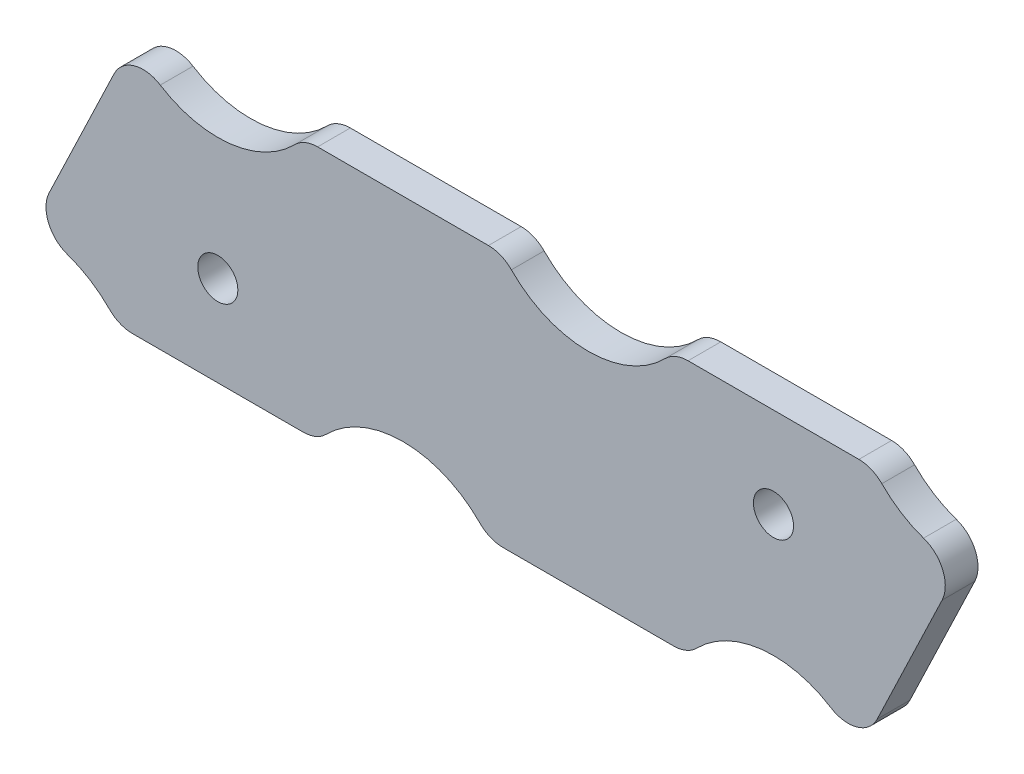
SolidWorks part; units mm, degrees
material "3003-H14"
ref_plane "X-Y Datum" through (0, 0, 0) normal (0, 0, 1) x (1, 0, 0)
ref_plane "X-Z Datum" through (0, 0, 0) normal (0, 1, 0) x (1, 0, 0)
ref_plane "Y-Z Datum" through (0, 0, 0) normal (1, 0, 0) x (0, 0, -1)
sketch "Sketch3" plane through (0, 0, 0) normal (0, 0, 1) x (1, 0, 0)
  line L0 (10.775, 10.775) -> (22.275, 34.775) construction
  line L1 (0, 0) -> (156.4633, 0) construction
  line L2 (0, 0) -> (0, 56.3098) construction
  line L3 (0, 56.3098) -> (156.4633, 56.3098) construction
  line L4 (156.4633, 0) -> (156.4633, 56.3098) construction
  line L5 (33.775, 10.775) -> (45.275, 34.775) construction
  line L6 (56.775, 10.775) -> (68.275, 34.775) construction
  line L7 (16.525, 22.775) -> (62.525, 22.775) construction
  line L8 (33.775, 10.775) -> (22.275, 34.775) construction
  line L9 (45.275, 34.775) -> (56.775, 10.775) construction
  line L10 (10.775, 10.775) -> (33.775, 10.775) construction
  line L11 (56.775, 10.775) -> (33.775, 10.775) construction
  line L12 (22.275, 34.775) -> (45.275, 34.775) construction
  line L13 (68.275, 34.775) -> (45.275, 34.775) construction
  line L14 (22.275, 34.775) -> (22.275, 10.775) construction
  line L15 (45.275, 10.775) -> (45.275, 34.775) construction
  line L16 (33.775, 10.775) -> (33.775, 34.775) construction
  line L17 (56.775, 34.775) -> (56.775, 10.775) construction
  line L18 (13.4804, 9.4786) -> (24.9804, 33.4786)
  line L19 (36.4804, 9.4786) -> (47.9804, 33.4786)
  line L20 (59.4804, 9.4786) -> (70.9804, 33.4786)
  line L21 (8.0696, 12.0714) -> (19.5696, 36.0714)
  line L22 (31.0696, 12.0714) -> (42.5696, 36.0714)
  line L23 (54.0696, 12.0714) -> (65.5696, 36.0714)
  line L24 (17.8152, 18.525) -> (57.1619, 18.525)
  line L25 (21.8881, 27.025) -> (61.2348, 27.025)
  line L26 (16.525, 27.025) -> (62.525, 27.025) construction
  line L27 (16.525, 18.525) -> (62.525, 18.525) construction
  line L28 (16.0692, 14.8813) -> (28.4808, 14.8813)
  line L29 (39.9808, 30.6687) -> (27.5692, 30.6687)
  line L48 (56.775, 10.775) -> (68.275, 10.775) construction
  line L49 (68.275, 10.775) -> (68.275, 34.775) construction
  line L50 (62.9808, 30.6687) -> (50.5692, 30.6687)
  line L51 (39.0692, 14.8813) -> (51.4808, 14.8813)
  circle A0 centre (10.775, 10.775) radius 10.775 construction
  circle A1 centre (33.775, 10.775) radius 10.775 construction
  circle A2 centre (22.275, 34.775) radius 10.775 construction
  circle A3 centre (45.275, 34.775) radius 10.775 construction
  circle A4 centre (68.275, 34.775) radius 10.775 construction
  circle A5 centre (56.775, 10.775) radius 10.775 construction
  circle A6 centre (10.775, 10.775) radius 4.7 construction
  circle A7 centre (33.775, 10.775) radius 4.7 construction
  circle A8 centre (56.775, 10.775) radius 4.7 construction
  circle A9 centre (68.275, 34.775) radius 4.7 construction
  circle A10 centre (45.275, 34.775) radius 4.7 construction
  circle A11 centre (22.275, 34.775) radius 4.7 construction
  circle A12 centre (22.275, 34.775) radius 6.7
  circle A13 centre (10.775, 10.775) radius 6.7
  circle A14 centre (33.775, 10.775) radius 6.7
  circle A15 centre (45.275, 34.775) radius 6.7
  circle A16 centre (68.275, 34.775) radius 6.7
  circle A17 centre (56.775, 10.775) radius 6.7
  circle A18 centre (125.775, 10.775) radius 10.775 construction
  circle A19 centre (102.775, 10.775) radius 10.775 construction
  circle A20 centre (79.775, 10.775) radius 10.775 construction
  circle A21 centre (91.275, 34.775) radius 10.775 construction
  circle A22 centre (114.275, 34.775) radius 10.775 construction
  circle A23 centre (137.275, 34.775) radius 10.775 construction
  dimension "D1" = 21.55
  dimension "D9" = 9.4
  dimension "D2" = 23
  dimension "D3" = 24
  dimension "D4" = 11.5
  dimension "D6" = 23
  dimension "D8" = 23
  dimension "D10" = 3
  dimension "D11" = 3
  dimension "D12" = 4.25
  dimension "D13" = 4.25
  dimension "D14" = 2
  dimension "D5" = 6
  dimension "D7" = 5
extrude "Boss-Extrude1" add sketch "Sketch3" along normal blind 2.032
ref_plane "Plane1" through (68.275, 0, 0) normal (1, 0, 0) x (0, 0, -1)
fillet "Fillet1" radius 2 12 edges at (62.9808, 30.6687, 1.016) (50.5692, 30.6687, 1.016) (39.9808, 30.6687, 1.016) (27.5692, 30.6687, 1.016) (16.0692, 14.8813, 1.016) (28.4808, 14.8813, 1.016) (39.0692, 14.8813, 1.016) (51.4808, 14.8813, 1.016) (68.3917, 28.076, 1.016) (62.0692, 14.8813, 1.016) (10.6583, 17.474, 1.016) (16.9808, 30.6687, 1.016)
sketch "Sketch4" plane through (0, 0, 2.032) normal (0, 0, 1) x (1, 0, 0)
  circle A0 centre (22.275, 20.4921) radius 1.2446
  circle A1 centre (56.775, 25.0579) radius 1.2446
  point P0 (56.775, 25.0579)
  point P1 (22.275, 20.4921)
  dimension "D1" = 2.4892
extrude "Cut-Extrude1" cut sketch "Sketch4" against normal through all
